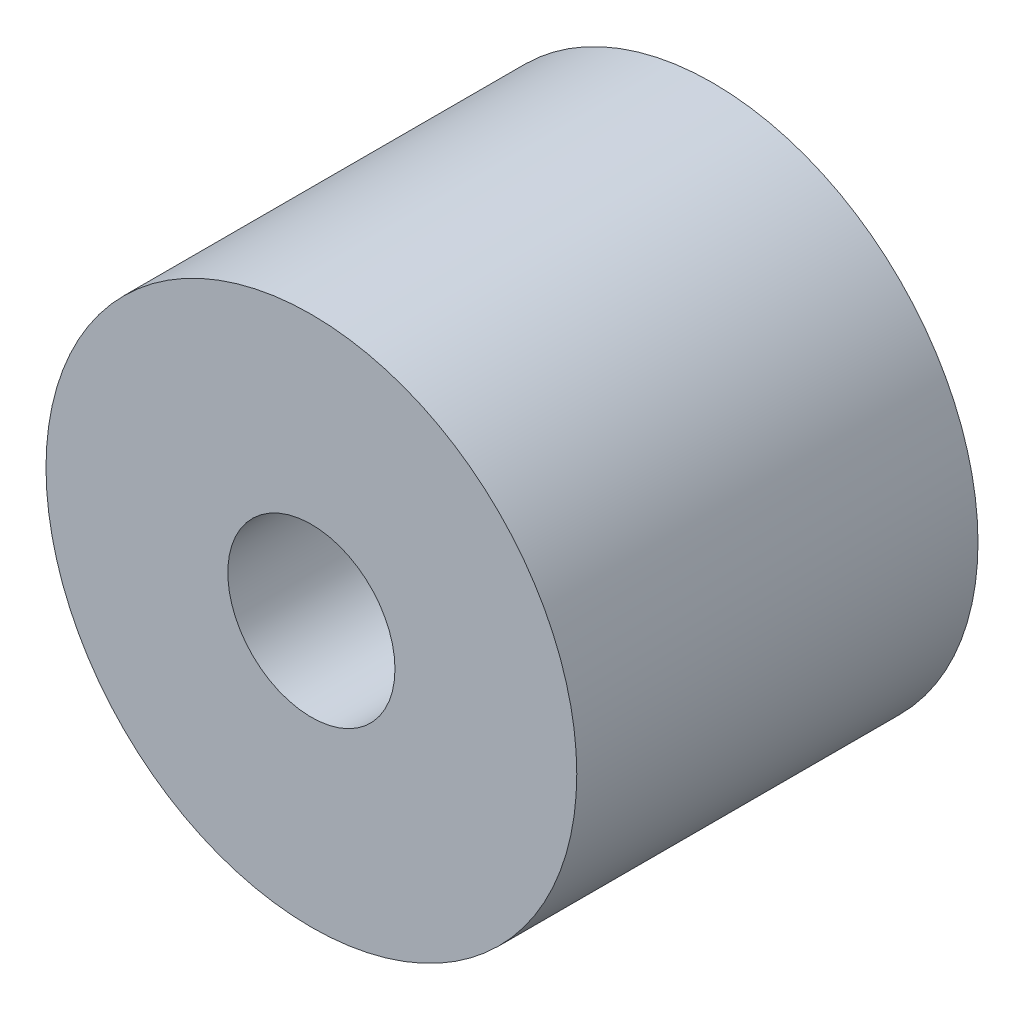
SolidWorks part; units mm, degrees
ref_plane "Front Plane" through (0, 0, 0) normal (0, 0, 1) x (1, 0, 0)
ref_plane "Top Plane" through (0, 0, 0) normal (0, 1, 0) x (1, 0, 0)
ref_plane "Right Plane" through (0, 0, 0) normal (1, 0, 0) x (0, 0, -1)
sketch "Sketch1" plane through (0, 0, 0) normal (0, 0, 1) x (1, 0, 0)
  circle A0 centre (0, 0) radius 3.9688
  dimension "D1" = 7.9375
extrude "Boss-Extrude1" add sketch "Sketch1" along normal blind 6
hole_wizard "Tap Drill for M3x0.5 Tap1" positions "Sketch2" profile "Sketch3" hole size "M3x0.5" standard "ANSI Metric" end condition through all
sketch "Sketch2" plane through (0, 0, 6) normal (0, 0, 1) x (1, 0, 0)
  point P0 (0, 0)
sketch "Sketch3" plane through (0, 0, 6) normal (1, 0, 0) x (0, -1, 0)
  line L0 (0, 0) -> (0, 6)
  line L1 (0, 6) -> (1.25, 6)
  line L2 (1.25, 6) -> (1.25, 0)
  line L5 (1.25, 0) -> (0, 0)
  line L11 (0, -6.35) -> (0, 107.95) construction
  dimension "Thru Hole Dia." = 2.5
  dimension "Thru Hole Depth" = 6
